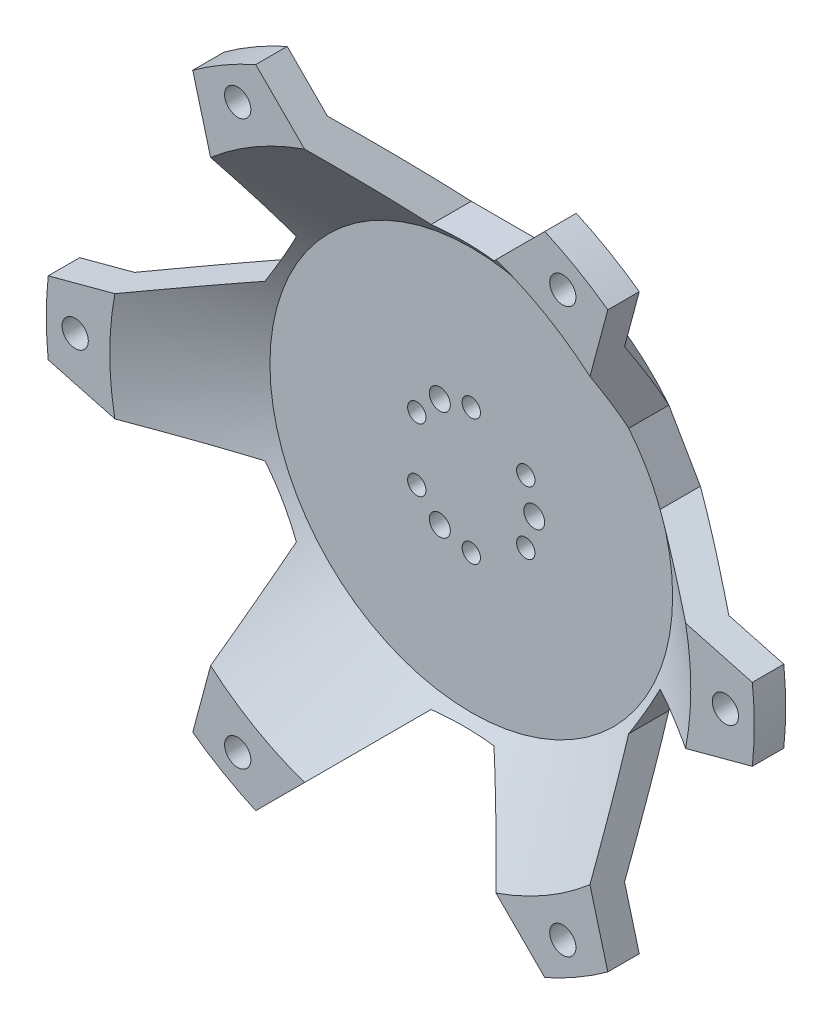
SolidWorks part; units mm, degrees
other "Markup1"
sketch "Sketch62" plane through (-128.5, -128.5, 146.8) normal (-0.0672, -0.6619, 0.7466) x (0.996, 0, 0.0896)
other "Markup2"
sketch "Sketch87" plane through (-128.5, 200.1498, -230) normal (-0.7911, 0.6051, -0.0891) x (-0.112, 0, 0.9937)
ref_plane "Front" through (0, 0, 0) normal (0, 0, 1) x (1, 0, 0)
ref_plane "Top" through (0, 0, 0) normal (0, 1, 0) x (1, 0, 0)
ref_plane "Right" through (0, 0, 0) normal (1, 0, 0) x (0, 0, -1)
sketch "Sketch51" plane through (0, 0, 0) normal (1, 0, 0) x (0, 0, -1)
  line L0 (-13.5434, 57.5) -> (0, 40.5)
  line L2 (0, 40.5) -> (0, 0)
  line L4 (0, 0) -> (117.0262, 0) construction
  line L6 (-19.5434, 55.4022) -> (-6, 38.4022)
  line L7 (-6, 38.4022) -> (-6, 0)
  line L8 (-18.2362, 53.7614) -> (-6, 38.4022) construction
  line L10 (0, 0) -> (-6, 0)
  line L11 (-13.5434, 57.5) -> (-13.5434, 67.5)
  line L13 (-13.5434, 67.5) -> (-19.5434, 67.5)
  line L14 (-19.5434, 67.5) -> (-19.5434, 55.4022)
  dimension "D2" = 13.5434
  dimension "D3" = 135
  dimension "D4" = 6
  dimension "D5" = 10
  dimension "D6" = 81
  dimension "D1" = 6
revolve "Revolve2" add sketch "Sketch51" angle 360 about L4
sketch "Sketch52" plane through (0, 0, 13.5434) normal (0, 0, -1) x (-1, 0, 0)
  line L2 (50.5181, 87.5) -> (0, 0) construction
  line L3 (0, 0) -> (-47.767, 82.7348) construction
  line L4 (-37.2958, 71.3489) -> (-6, 40.0531)
  line L5 (-6, 40.0531) -> (6, 40.0531)
  line L7 (0, 0) -> (0, 200.1498) construction
  line L8 (-37.2958, 71.3489) -> (37.2958, 71.3489)
  line L9 (37.2958, 71.3489) -> (6, 40.0531)
  line L10 (31.687, 25.2227) -> (37.687, 14.8304)
  line L11 (80.4379, 3.3753) -> (37.687, 14.8304)
  line L12 (43.1421, 67.9736) -> (80.4379, 3.3753)
  line L13 (43.1421, 67.9736) -> (31.687, 25.2227)
  line L14 (37.687, -14.8304) -> (31.687, -25.2227)
  line L15 (43.1421, -67.9736) -> (31.687, -25.2227)
  line L16 (80.4379, -3.3753) -> (43.1421, -67.9736)
  line L17 (80.4379, -3.3753) -> (37.687, -14.8304)
  line L18 (6, -40.0531) -> (-6, -40.0531)
  line L19 (-37.2958, -71.3489) -> (-6, -40.0531)
  line L20 (37.2958, -71.3489) -> (-37.2958, -71.3489)
  line L21 (37.2958, -71.3489) -> (6, -40.0531)
  line L22 (-31.687, -25.2227) -> (-37.687, -14.8304)
  line L23 (-80.4379, -3.3753) -> (-37.687, -14.8304)
  line L24 (-43.1421, -67.9736) -> (-80.4379, -3.3753)
  line L25 (-43.1421, -67.9736) -> (-31.687, -25.2227)
  line L26 (-37.687, 14.8304) -> (-31.687, 25.2227)
  line L27 (-43.1421, 67.9736) -> (-31.687, 25.2227)
  line L28 (-80.4379, 3.3753) -> (-43.1421, 67.9736)
  line L29 (-80.4379, 3.3753) -> (-37.687, 14.8304)
  circle A0 centre (0, 0) radius 40.5 construction
  point P12 (0, 40.0531)
  point P13 (0, 71.3489)
  dimension "D1" = 135
  dimension "D2" = 6
  dimension "D4" = 30
  dimension "D5" = 30
  dimension "D3" = 6
extrude "Cut-Extrude15" cut sketch "Sketch52" against normal through all both and the other way through all
sketch "Sketch53" plane through (0, 0, 13.5434) normal (0, 0, -1) x (-1, 0, 0)
  circle A0 centre (62, 0) radius 2.5
  circle A1 centre (31, -53.6936) radius 2.5
  circle A2 centre (-31, -53.6936) radius 2.5
  circle A3 centre (-62, 0) radius 2.5
  circle A4 centre (-31, 53.6936) radius 2.5
  circle A5 centre (31, 53.6936) radius 2.5
  circle A6 centre (0, 0) radius 62 construction
  dimension "D1" = 5
  dimension "D2" = 62
  dimension "D3" = 6
extrude "Cut-Extrude16" cut sketch "Sketch53" against normal through all
sketch "Sketch88" plane through (0, 0, 0) normal (0, 0, -1) x (-1, 0, 0)
  line L0 (0, -12) -> (10.3923, -6) construction
  line L1 (6, -10.3923) -> (0, 0) construction
  circle A0 centre (0, 12) radius 1.75
  circle A1 centre (10.3923, 6) radius 1.75
  circle A2 centre (10.3923, -6) radius 1.75
  circle A3 centre (0, -12) radius 1.75
  circle A4 centre (-10.3923, -6) radius 1.75
  circle A5 centre (-10.3923, 6) radius 1.75
  circle A6 centre (6, -10.3923) radius 2
  circle A7 centre (-12, 0) radius 2
  circle A8 centre (6, 10.3923) radius 2
  point P15 (0, 0)
  point P18 (5.1962, -9)
  point P23 (0, 0)
  dimension "D1" = 3.5
  dimension "D2" = 12
  dimension "D4" = 4
  dimension "D5" = 12
  dimension "D3" = 6
  dimension "D6" = 3
extrude "Cut-Extrude17" cut sketch "Sketch88" against normal through all
